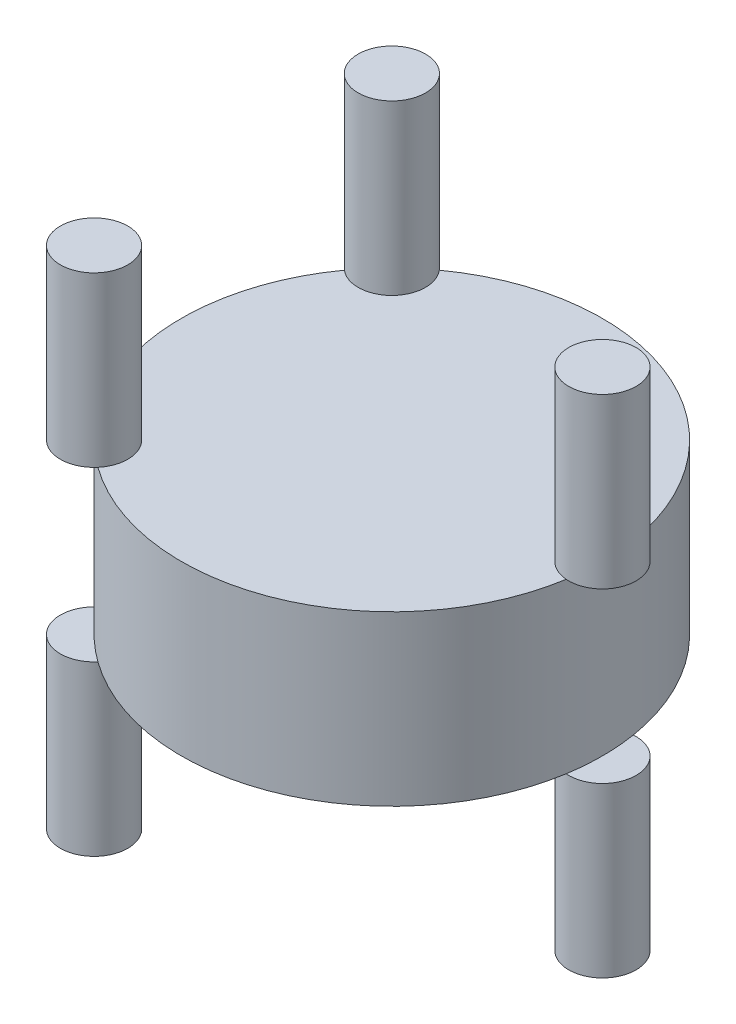
SolidWorks part; units mm, degrees
ref_plane "Front Plane" through (0, 0, 0) normal (0, 0, 1) x (1, 0, 0)
ref_plane "Top Plane" through (0, 0, 0) normal (0, 1, 0) x (1, 0, 0)
ref_plane "Right Plane" through (0, 0, 0) normal (1, 0, 0) x (0, 0, -1)
sketch "Sketch7" plane through (0, 0, 0) normal (0, 1, 0) x (1, 0, 0)
  circle A0 centre (0, 0) radius 12.5
  dimension "D1" = 25
extrude "Boss-Extrude2" add sketch "Sketch7" along normal blind 10
sketch "Sketch8" plane through (0, 10, 0) normal (0, 1, 0) x (1, 0, 0)
  line L0 (0, -13.5447) -> (0, 12.8126) construction
  line L1 (-13.7016, 0) -> (13.7714, 0) construction
  line L2 (0, 0) -> (-9.5104, 9.5104) construction
  circle A0 centre (-8.8388, 8.8388) radius 2
  circle A1 centre (0, 0) radius 12.5 construction
  dimension "D2" = 4
  dimension "D1" = 45
extrude "Boss-Extrude3" add sketch "Sketch8" along normal blind 10
mirror "Mirror1" about plane through (0, 0, 0) normal (0, 0, 1) of "Boss-Extrude3"
sketch "Sketch9" plane through (0, 10, 0) normal (0, 1, 0) x (1, 0, 0)
  line L0 (14.2246, 0) -> (-1.0808, 0) construction
  circle A0 centre (12.5, 0) radius 2
  arc A1 (-7.316, -10.1354) -> (-7.316, 10.1354) centre (0, 0) ccw construction
  dimension "D1" = 4
extrude "Boss-Extrude4" add sketch "Sketch9" along normal blind 10
sketch "Sketch12" plane through (0, 0, 0) normal (0, -1, 0) x (1, 0, 0)
  circle A0 centre (-8.8388, -8.8388) radius 2
  arc A1 (-10.1354, -7.316) -> (-7.316, -10.1354) centre (0, 0) ccw construction
  dimension "D1" = 4
extrude "Boss-Extrude5" add sketch "Sketch12" along normal blind 10
mirror "Mirror3" about plane through (0, 0, 0) normal (0, 0, 1) of "Boss-Extrude5"
sketch "Sketch13" plane through (0, 0, 0) normal (0, -1, 0) x (-1, 0, 0)
  circle A0 centre (-12.5, 0) radius 2
  arc A1 (7.316, 10.1354) -> (7.316, -10.1354) centre (0, 0) ccw construction
  dimension "D1" = 4
extrude "Boss-Extrude6" add sketch "Sketch13" along normal blind 10
